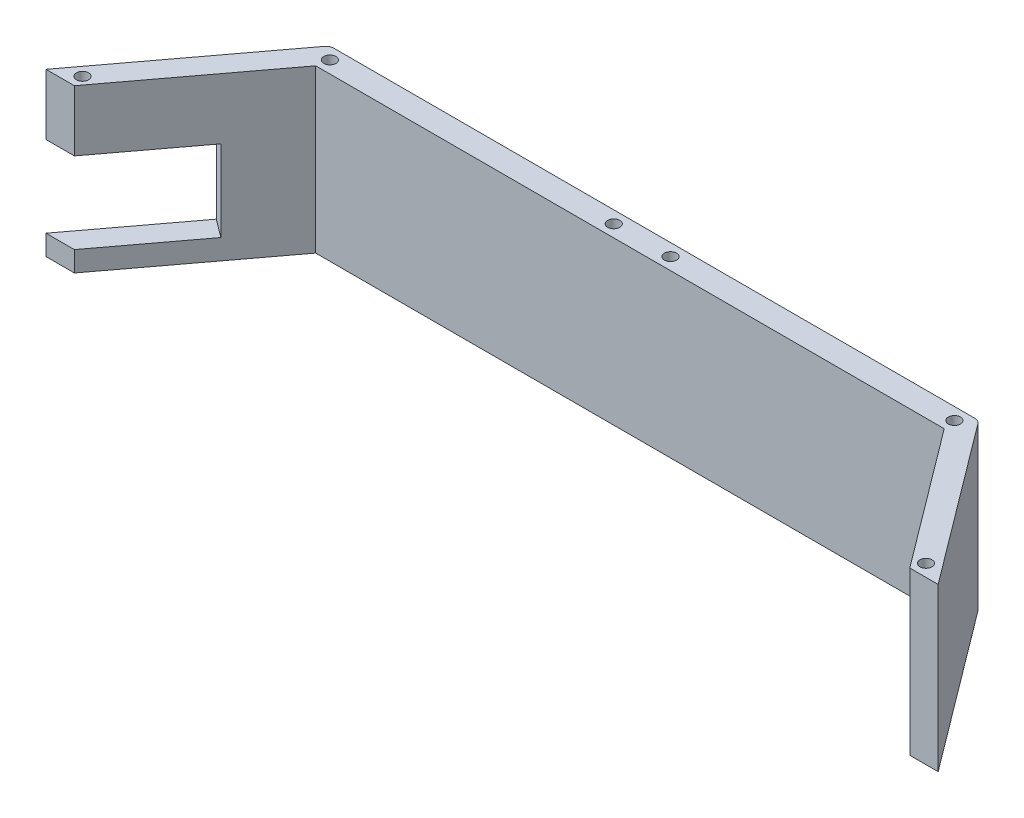
SolidWorks part; units mm, degrees
ref_plane "Front Plane" through (0, 0, 0) normal (0, 0, 1) x (1, 0, 0)
ref_plane "Top Plane" through (0, 0, 0) normal (0, 1, 0) x (1, 0, 0)
ref_plane "Right Plane" through (0, 0, 0) normal (1, 0, 0) x (0, 0, -1)
sketch "Sketch1" plane through (0, 0, 0) normal (0, 1, 0) x (1, 0, 0)
  line L0 (-110, 0) -> (-80, 40)
  line L1 (-80, 40) -> (80, 40)
  line L3 (77.5, 34) -> (-77.5, 34)
  line L4 (-77.5, 34) -> (-103, 0)
  line L5 (-103, 0) -> (-110, 0)
  line L6 (0, -55) -> (0, 55) construction
  line L7 (103, 0) -> (110, 0)
  line L8 (77.5, 34) -> (103, 0)
  line L9 (110, 0) -> (80, 40)
  dimension "D1" = 6
  dimension "D2" = 7
  dimension "D3" = 40
  dimension "D4" = 30
extrude "Boss-Extrude1" add sketch "Sketch1" along normal mid plane 40
sketch "Sketch2" plane through (0, 20, 0) normal (0, 1, 0) x (1, 0, 0)
  line L1 (-80, 40) -> (-110, 0) construction
  line L2 (80, 40) -> (-80, 40) construction
  line L3 (0, -22) -> (0, 22) construction
  circle A0 centre (-104, 3) radius 1.5
  circle A1 centre (-77, 37) radius 1.5
  circle A2 centre (-7, 37) radius 1.5
  circle A3 centre (7, 37) radius 1.5
  circle A4 centre (77, 37) radius 1.5
  circle A5 centre (104, 3) radius 1.5
  dimension "D2" = 3
  dimension "D3" = 3
  dimension "D5" = 3
  dimension "D1" = 70
  dimension "D4" = 7
  dimension "D6" = 3
  dimension "D7" = 3
  dimension "D8" = 3
  dimension "D9" = 37
extrude "Cut-Extrude1" cut sketch "Sketch2" against normal blind 5
fillet "Fillet1" radius 2 2 edges at (80, 0, -40) (-80, 0, -40)
sketch "Sketch3" plane through (-70.4, 0, -52.8) normal (-0.8, 0, -0.6) x (-0.6, 0, 0.8)
  line L1 (66, -15) -> (36, -15)
  line L2 (66, -15) -> (66, 5)
  line L3 (66, 5) -> (36, 5)
  line L4 (36, -15) -> (36, 5)
  line L5 (17, 20) -> (66, 20) construction
  dimension "D1" = 15
  dimension "D2" = 20
  dimension "D3" = 30
extrude "Cut-Extrude2" cut sketch "Sketch3" against normal blind 10
